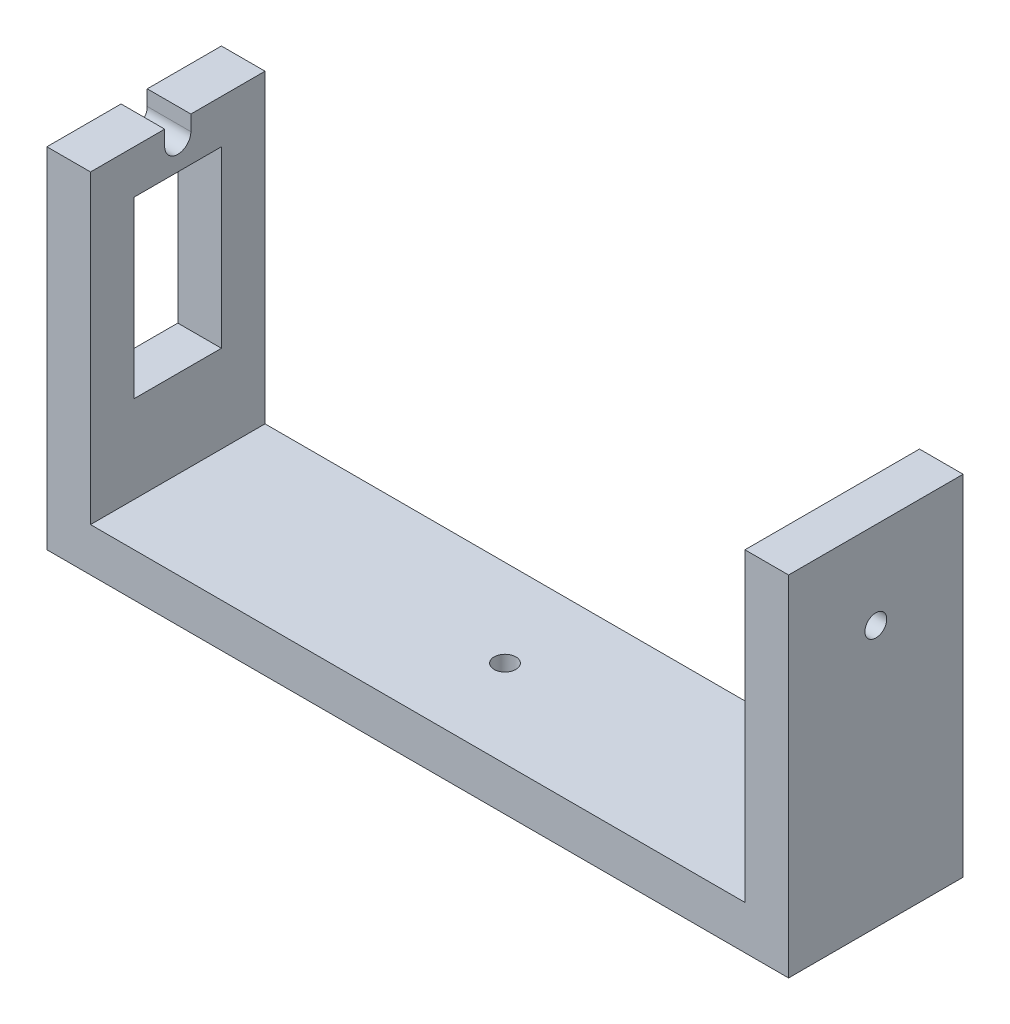
SolidWorks part; units mm, degrees
other "Markup1"
sketch "Sketch5" plane through (-85, 80, 20) normal (-0.8857, 0.2194, 0.4092) x (0.4097, -0.0452, 0.9111)
material "PE High Density"
ref_plane "Front Plane" through (0, 0, 0) normal (0, 0, 1) x (1, 0, 0)
ref_plane "Top Plane" through (0, 0, 0) normal (0, 1, 0) x (1, 0, 0)
ref_plane "Right Plane" through (0, 0, 0) normal (1, 0, 0) x (0, 0, -1)
sketch "Sketch1" plane through (0, 0, 0) normal (0, 1, 0) x (1, 0, 0)
  line L1 (-85, -20) -> (85, -20)
  line L2 (-85, -20) -> (-85, 20)
  line L3 (-85, 20) -> (85, 20)
  line L4 (85, -20) -> (85, 20)
  line L5 (-85, -20) -> (85, 20) construction
  line L6 (-85, 20) -> (85, -20) construction
  circle A0 centre (0, 0) radius 2.5
  point P0 (0, 0)
  dimension "D3" = 5
  dimension "D1" = 40
  dimension "D2" = 170
extrude "Boss-Extrude1" add sketch "Sketch1" along normal blind 10
sketch "Sketch2" plane through (0, 10, 0) normal (0, 1, 0) x (1, 0, 0)
  line L0 (-85, -20) -> (85, -20) construction
  line L1 (85, 20) -> (75, 20)
  line L2 (85, 20) -> (85, -20)
  line L3 (85, -20) -> (75, -20)
  line L4 (75, 20) -> (75, -20)
  line L5 (0, 0) -> (0, 16.482) construction
  line L6 (-85, -20) -> (-75, -20)
  line L7 (-75, 20) -> (-75, -20)
  line L8 (-85, 20) -> (-75, 20)
  line L9 (-85, 20) -> (-85, -20)
  dimension "D1" = 10
extrude "Boss-Extrude2" add sketch "Sketch2" along normal blind 70
sketch "Sketch3" plane through (-85, 0, 0) normal (-1, 0, 0) x (0, 0, 1)
  line L0 (-20, 80) -> (20, 80) construction
  line L1 (10, 70) -> (-10, 70)
  line L2 (10, 70) -> (10, 30)
  line L3 (10, 30) -> (-10, 30)
  line L4 (-10, 70) -> (-10, 30)
  line L5 (0, 80) -> (0, 76.5) construction
  line L8 (3, 80) -> (3, 76.5)
  line L9 (-3, 80) -> (-3, 76.5)
  arc A2 (3, 80) -> (-3, 80) centre (0, 80) ccw
  arc A3 (-3, 76.5) -> (3, 76.5) centre (0, 76.5) ccw
  point P6 (0, 80)
  point P7 (0, 70)
  point P11 (0, 78.25)
  dimension "D5" = 3
  dimension "D1" = 10
  dimension "D2" = 20
  dimension "D3" = 40
  dimension "D4" = 3.5
extrude "Cut-Extrude1" cut sketch "Sketch3" against normal blind 50
sketch "Sketch4" plane through (85, 0, 0) normal (1, 0, 0) x (0, 0, -1)
  line L0 (-20, 80) -> (20, 80) construction
  circle A0 centre (0, 60) radius 2.5
  point P5 (0, 80)
  dimension "D1" = 5
  dimension "D2" = 20
extrude "Cut-Extrude2" cut sketch "Sketch4" against normal blind 24
